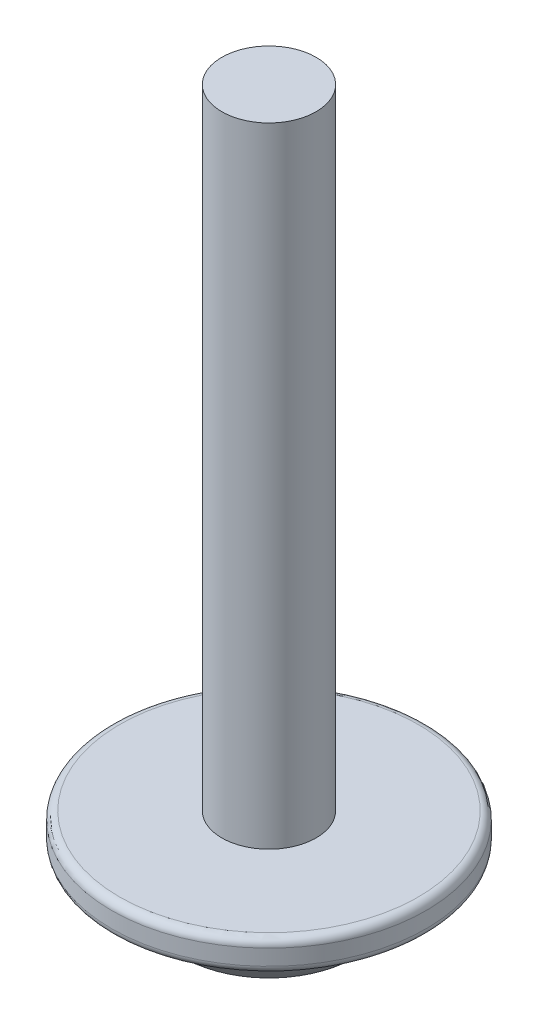
SolidWorks part; units mm, degrees
material "AISI 4140 Steel, quenched & tempered"
ref_plane "Front Plane" through (0, 0, 0) normal (1, 0, 0) x (0, 1, 0)
ref_plane "Top Plane" through (0, 0, 0) normal (0, 0, 1) x (0, 1, 0)
ref_plane "Right Plane" through (0, 0, 0) normal (0, 1, 0) x (-1, 0, 0)
sketch "Sketch1" plane through (0, 0, 0) normal (1, 0, 0) x (0, 1, 0)
  line L0 (-21.912, 0) -> (25.327, 0) construction
  line L1 (0, 30.1451) -> (0, -21.3064) construction
  line L2 (0, 3) -> (40, 3)
  line L3 (40, 3) -> (40, 0)
  line L4 (40, 0) -> (0, 0)
  line L5 (0, 0) -> (0, 3)
  line L7 (0, 10) -> (-2, 10)
  line L8 (-2, 10) -> (-2, 0)
  line L9 (-2, 0) -> (0, 0)
  line L10 (0, 10) -> (0, 3)
  line L11 (-7, 0) -> (-2, 0)
  arc A1 (-2, 8) -> (-7, 0) centre (0.9793, 0.5755) ccw
  dimension "D5" = 5
  dimension "D7" = 8
  dimension "D1" = 6
  dimension "D2" = 40
  dimension "D3" = 2
  dimension "D4" = 20
  dimension "D6" = 16
revolve "Revolve1" add sketch "Sketch1" angle 360 about L0
sketch "Sketch2" plane through (0, -2, 0) normal (0, -1, 0) x (1, 0, 0)
  line L7 (2, -3.4641) -> (4, 0)
  line L8 (4, 0) -> (2, 3.4641)
  line L9 (2, 3.4641) -> (-2, 3.4641)
  line L10 (-2, 3.4641) -> (-4, 0)
  line L11 (-4, 0) -> (-2, -3.4641)
  line L12 (-2, -3.4641) -> (2, -3.4641)
  circle A0 centre (0, 0) radius 4 construction
  dimension "D1" = 4
extrude "Cut-Extrude1" cut sketch "Sketch2" along normal blind 10 from offset 1
fillet "Fillet1" radius 0.5 20 edges at (0, 0, -10) (0, -2, -10) (0, -3, -3.4641) (0, -3, 3.4641) (0.4257, -6.4709, 3.4641) (-0.4257, -6.4709, -3.4641) (3, -3, -1.7321) (3, -3, 1.7321) (-3, -3, 1.7321) (-3, -3, -1.7321) (-2, -4.6253, -3.4641) (-2, -4.6253, 3.4641) (2, -4.6253, 3.4641) (4, -4.6253, 0) (2, -4.6253, -3.4641) (-2.5442, -6.4343, -2.5215) (-3.4558, -6.4343, 0.9426) (2.5442, -6.4343, 2.5215) (3.4558, -6.4343, -0.9426) (-4, -4.6253, 0)
